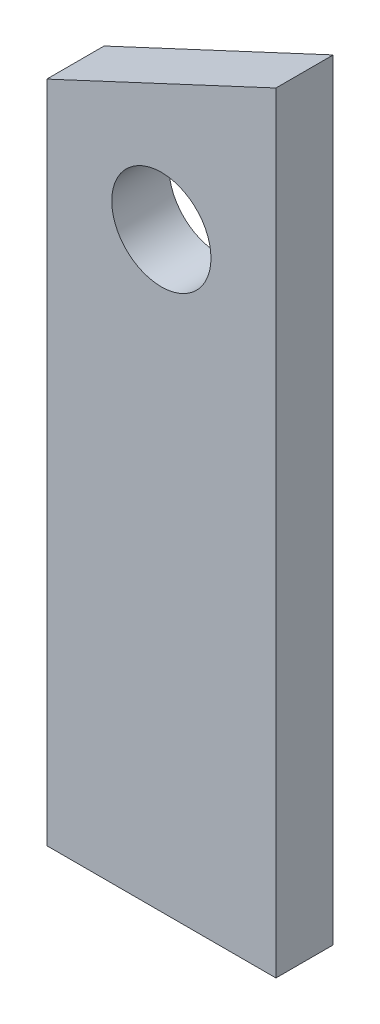
SolidWorks part; units mm, degrees
material "AISI 1020 Steel, Cold Rolled"
ref_plane "Front Plane" through (0, 0, 0) normal (0, 0, 1) x (1, 0, 0)
ref_plane "Top Plane" through (0, 0, 0) normal (0, 1, 0) x (1, 0, 0)
ref_plane "Right Plane" through (0, 0, 0) normal (1, 0, 0) x (0, 0, -1)
sketch "Sketch2" plane through (0, 0, 0) normal (0, 1, 0) x (1, 0, 0)
  line L1 (0, 0) -> (12.7, 0)
  line L2 (0, 0) -> (0, -3.175)
  line L3 (0, -3.175) -> (12.7, -3.175)
  line L4 (12.7, 0) -> (12.7, -3.175)
  dimension "D1" = 12.7
  dimension "D2" = 3.175
extrude "Boss-Extrude1" add sketch "Sketch2" along normal blind 63.5
sketch "Sketch3" plane through (0, 0, 3.175) normal (0, 0, -1) x (-1, 0, 0)
  line L0 (-6.35, 63.5) -> (-6.35, 0) construction
  line L1 (-12.7, 63.5) -> (0, 63.5) construction
  line L2 (-12.7, 0) -> (0, 0) construction
  line L3 (-12.7231, 42.732) -> (0, 36.7991)
  line L4 (-12.7231, 42.732) -> (-18.0904, 31.2219) construction
  line L5 (51.6247, 12.7261) -> (-12.7231, 42.732) construction
  line L6 (0, 63.5) -> (0, 0) construction
  line L7 (0, 36.7991) -> (0, 63.5)
  line L8 (0, 63.5) -> (-12.7, 63.5)
  line L9 (-12.7, 63.5) -> (-12.7231, 42.732)
  circle A0 centre (-6.35, 32.7508) radius 2.75
  dimension "D1" = 5.5
extrude "Cut-Extrude1" cut sketch "Sketch3" along normal up to next
